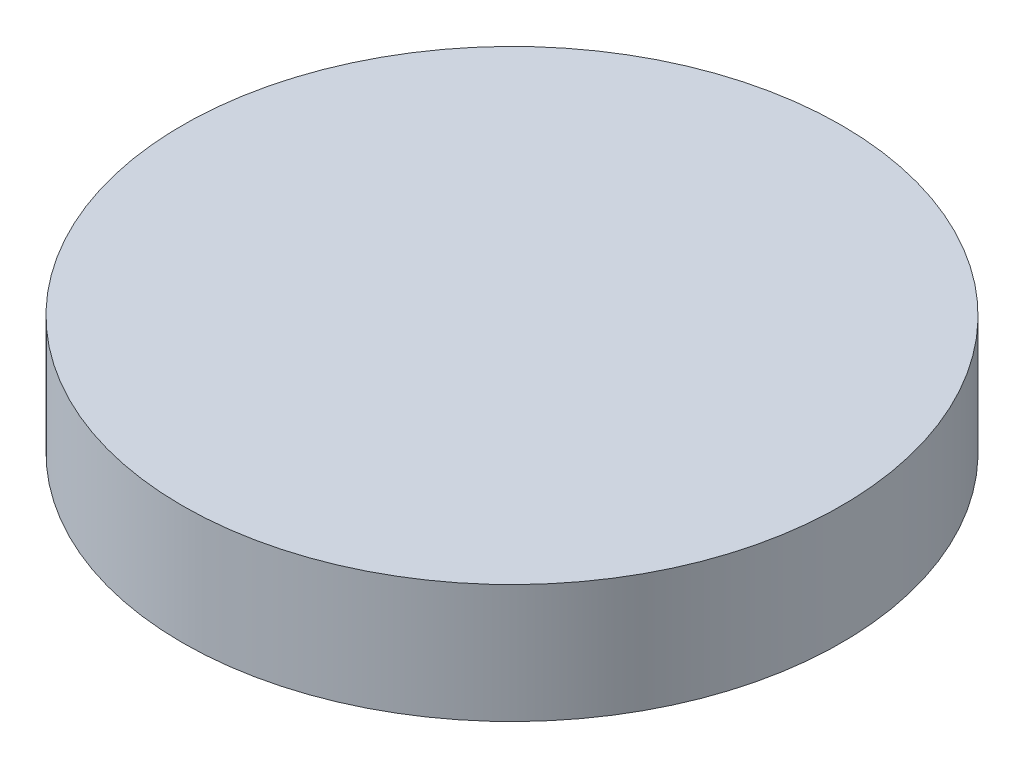
SolidWorks part; units mm, degrees
ref_plane "前视基准面" through (0, 0, 0) normal (0, 0, 1) x (1, 0, 0)
ref_plane "上视基准面" through (0, 0, 0) normal (0, 1, 0) x (1, 0, 0)
ref_plane "右视基准面" through (0, 0, 0) normal (1, 0, 0) x (0, 0, -1)
other "Configuration Table"
sketch "草图1" plane through (0, 0, 0) normal (0, 1, 0) x (1, 0, 0)
  circle A0 centre (0, 0) radius 12.5
  dimension "D1" = 25
extrude "凸台-拉伸1" add sketch "草图1" along normal blind 4.5
